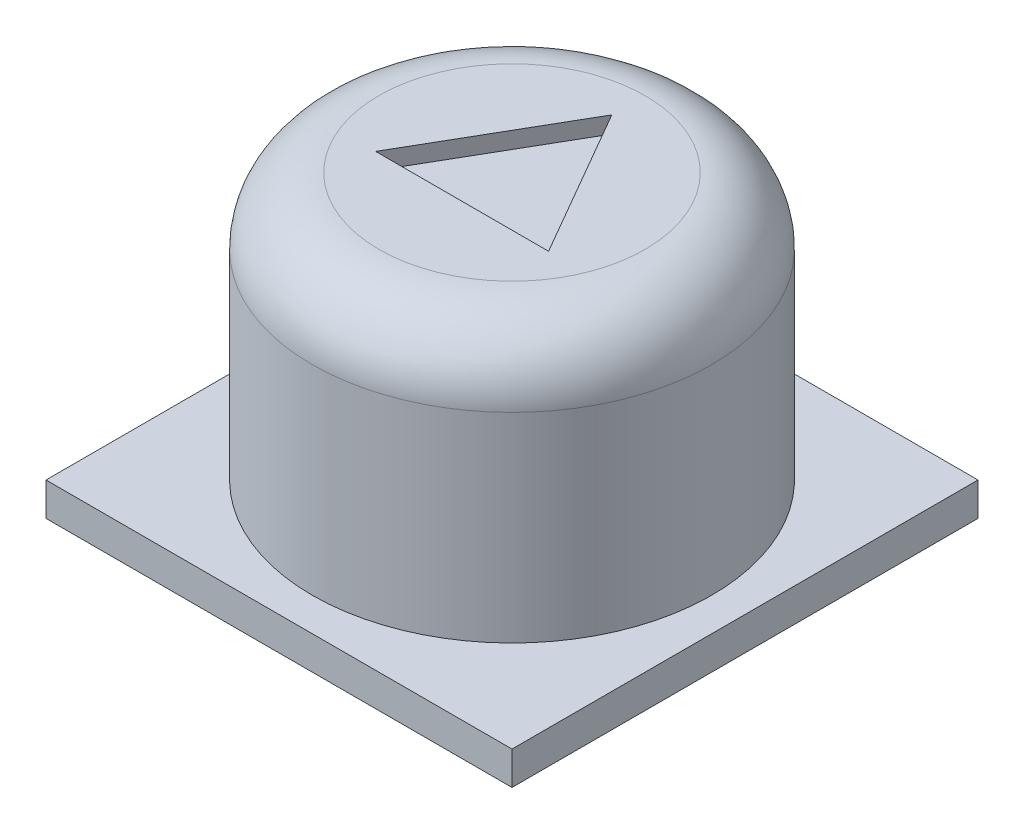
SolidWorks part; units mm, degrees
material "ABS"
ref_plane "Alzado" through (0, 0, 0) normal (0, 0, 1) x (1, 0, 0)
ref_plane "Planta" through (0, 0, 0) normal (0, 1, 0) x (1, 0, 0)
ref_plane "Vista lateral" through (0, 0, 0) normal (1, 0, 0) x (0, 0, -1)
sketch "Croquis1" plane through (0, 0, 0) normal (0, 1, 0) x (1, 0, 0)
  line L1 (7, -7) -> (-7, -7)
  line L2 (7, -7) -> (7, 7)
  line L3 (7, 7) -> (-7, 7)
  line L4 (-7, -7) -> (-7, 7)
  line L5 (7, -7) -> (-7, 7) construction
  line L6 (7, 7) -> (-7, -7) construction
  point P0 (0, 0)
  dimension "D1" = 14
  dimension "D2" = 14
extrude "Saliente-Extruir1" add sketch "Croquis1" along normal blind 1
sketch "Croquis2" plane through (0, 0, 0) normal (0, -1, 0) x (1, 0, 0)
  line L1 (-2, 2) -> (2, 2)
  line L2 (-2, 2) -> (-2, -2)
  line L3 (-2, -2) -> (2, -2)
  line L4 (2, 2) -> (2, -2)
  line L5 (-2, 2) -> (2, -2) construction
  line L6 (-2, -2) -> (2, 2) construction
  point P0 (0, 0)
  dimension "D1" = 4
  dimension "D2" = 4
extrude "Cortar-Extruir1" cut sketch "Croquis2" against normal blind 1
sketch "Croquis3" plane through (0, 0, 0) normal (0, -1, 0) x (1, 0, 0)
  line L1 (-3, 3) -> (3, 3)
  line L2 (-3, 3) -> (-3, -3)
  line L3 (-3, -3) -> (3, -3)
  line L4 (3, 3) -> (3, -3)
  line L5 (-3, 3) -> (3, -3) construction
  line L6 (-3, -3) -> (3, 3) construction
  point P0 (0, 0)
  dimension "D1" = 6
  dimension "D2" = 6
extrude "Saliente-Extruir3" add sketch "Croquis3" along normal blind 1
sketch "Croquis5" plane through (0, -1, 0) normal (0, -1, 0) x (1, 0, 0)
  line L1 (2, -2) -> (-2, -2)
  line L2 (2, -2) -> (2, 2)
  line L3 (2, 2) -> (-2, 2)
  line L4 (-2, -2) -> (-2, 2)
  line L5 (2, -2) -> (-2, 2) construction
  line L6 (2, 2) -> (-2, -2) construction
  point P0 (0, 0)
  dimension "D1" = 4
  dimension "D2" = 4
extrude "Cortar-Extruir3" cut sketch "Croquis5" against normal blind 1
sketch "Croquis6" plane through (0, 1, 0) normal (0, 1, 0) x (1, 0, 0)
  circle A0 centre (0, 0) radius 6
extrude "Saliente-Extruir4" add sketch "Croquis6" along normal blind 8
sketch "Croquis7" plane through (0, -1, 0) normal (0, -1, 0) x (1, 0, 0)
  line L1 (3, -3) -> (-3, -3)
  line L2 (3, -3) -> (3, 3)
  line L3 (3, 3) -> (-3, 3)
  line L4 (-3, -3) -> (-3, 3)
  line L5 (3, -3) -> (-3, 3) construction
  line L6 (3, 3) -> (-3, -3) construction
  point P0 (0, 0)
extrude "Cortar-Extruir4" cut sketch "Croquis7" against normal blind 2
sketch "Croquis8" plane through (0, 0, 0) normal (0, -1, 0) x (1, 0, 0)
  line L1 (7, -7) -> (-7, -7)
  line L2 (7, -7) -> (7, 7)
  line L3 (7, 7) -> (-7, 7)
  line L4 (-7, -7) -> (-7, 7)
  line L5 (7, -7) -> (-7, 7) construction
  line L6 (7, 7) -> (-7, -7) construction
  point P0 (0, 0)
extrude "Saliente-Extruir5" add sketch "Croquis8" against normal blind 1
sketch "Croquis9" plane through (0, 0, 0) normal (0, -1, 0) x (1, 0, 0)
  line L1 (3, -3) -> (-3, -3)
  line L2 (3, -3) -> (3, 3)
  line L3 (3, 3) -> (-3, 3)
  line L4 (-3, -3) -> (-3, 3)
  line L5 (3, -3) -> (-3, 3) construction
  line L6 (3, 3) -> (-3, -3) construction
  point P0 (0, 0)
  dimension "D1" = 6
  dimension "D2" = 6
extrude "Saliente-Extruir6" add sketch "Croquis9" along normal blind 2
sketch "Croquis10" plane through (0, -2, 0) normal (0, -1, 0) x (1, 0, 0)
  line L1 (2, -2) -> (-2, -2)
  line L2 (2, -2) -> (2, 2)
  line L3 (2, 2) -> (-2, 2)
  line L4 (-2, -2) -> (-2, 2)
  line L5 (2, -2) -> (-2, 2) construction
  line L6 (2, 2) -> (-2, -2) construction
  point P0 (0, 0)
  dimension "D1" = 4
  dimension "D2" = 4
extrude "Cortar-Extruir5" cut sketch "Croquis10" against normal blind 2
fillet "Redondeo2" radius 2 1 edges at (0, 9, 6)
sketch "Croquis11" plane through (0, 9, 0) normal (0, 1, 0) x (1, 0, 0)
  line L1 (0, 3) -> (-2.5981, -1.5)
  line L2 (-2.5981, -1.5) -> (2.5981, -1.5)
  line L3 (2.5981, -1.5) -> (0, 3)
  circle A0 centre (0, 0) radius 1.5 construction
extrude "Cortar-Extruir6" cut sketch "Croquis11" against normal blind 0.5
